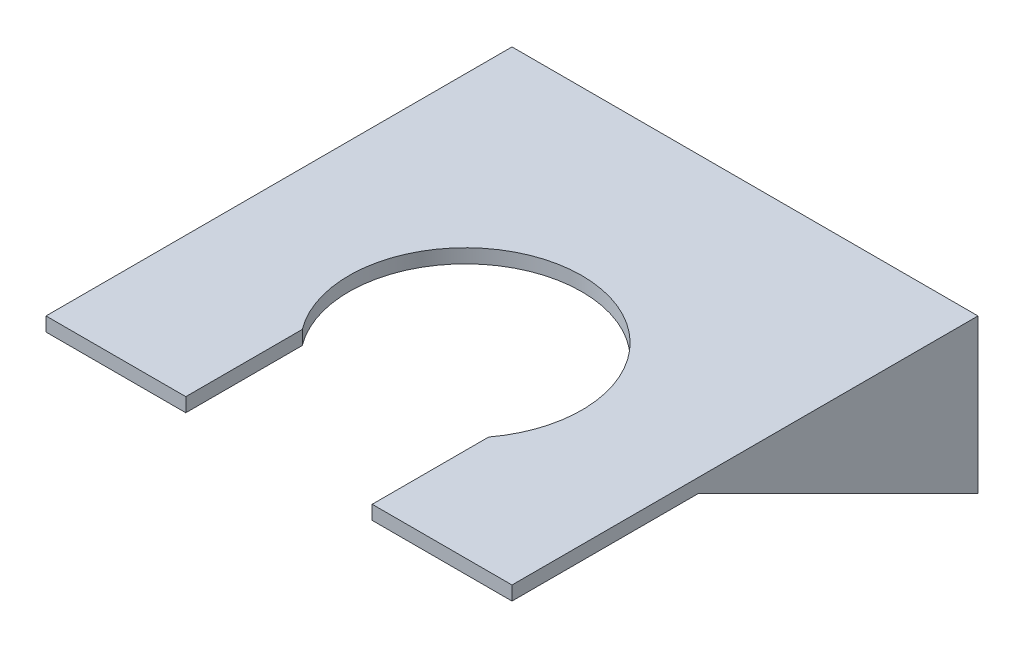
SolidWorks part; units mm, degrees
ref_plane "Front Plane" through (0, 0, 0) normal (0, 0, 1) x (1, 0, 0)
ref_plane "Top Plane" through (0, 0, 0) normal (0, 1, 0) x (1, 0, 0)
ref_plane "Right Plane" through (0, 0, 0) normal (1, 0, 0) x (0, 0, -1)
sketch "Sketch1" plane through (0, 0, 0) normal (0, 0, 1) x (1, 0, 0)
  line L1 (-25, -1.0618) -> (25, -1.0618)
  line L2 (-25, -1.0618) -> (-25, -2.5618)
  line L3 (-25, -2.5618) -> (25, -2.5618)
  line L4 (25, -1.0618) -> (25, -2.5618)
  point P6 (0, -1.0618)
  dimension "D1" = 1.5
  dimension "D3" = 50
extrude "Boss-Extrude1" add sketch "Sketch1" along normal blind 50
sketch "Sketch2" plane through (0, -1.0618, 0) normal (0, 1, 0) x (1, 0, 0)
  line L0 (-25, -30) -> (25, -30) construction
  line L1 (-25, -50) -> (-25, 0) construction
  line L2 (25, -50) -> (25, 0) construction
  line L3 (-10, -37.5) -> (-10, -50)
  line L5 (10, -37.5) -> (10, -50)
  line L6 (25, 0) -> (-25, 0) construction
  line L7 (-10, -50) -> (10, -50)
  arc A0 (10, -37.5) -> (-10, -37.5) centre (0, -30) ccw
  dimension "D2" = 25
  dimension "D1" = 30
  dimension "D3" = 10
  dimension "D4" = 10
extrude "Cut-Extrude1" cut sketch "Sketch2" against normal up to surface (1.5 mm away) up to face at (0, -2.5618, 25)
ref_plane "Plane4" through (-20, 0, 0) normal (-1, 0, 0) x (0, 0, 1)
sketch "Sketch4" plane through (-25, 0, 0) normal (-1, 0, 0) x (0, 0, 1)
  line L0 (0, -2.5618) -> (0, -17.5618)
  line L1 (0, -17.5618) -> (30, -2.5618)
  line L2 (50, -2.5618) -> (0, -2.5618) construction
  line L3 (30, -2.5618) -> (0, -2.5618)
  dimension "D1" = 15
  dimension "D2" = 30
extrude "Boss-Extrude2" add sketch "Sketch4" against normal blind 1.5
mirror "Mirror1" about plane through (0, 0, 0) normal (1, 0, 0) of "Boss-Extrude2"
